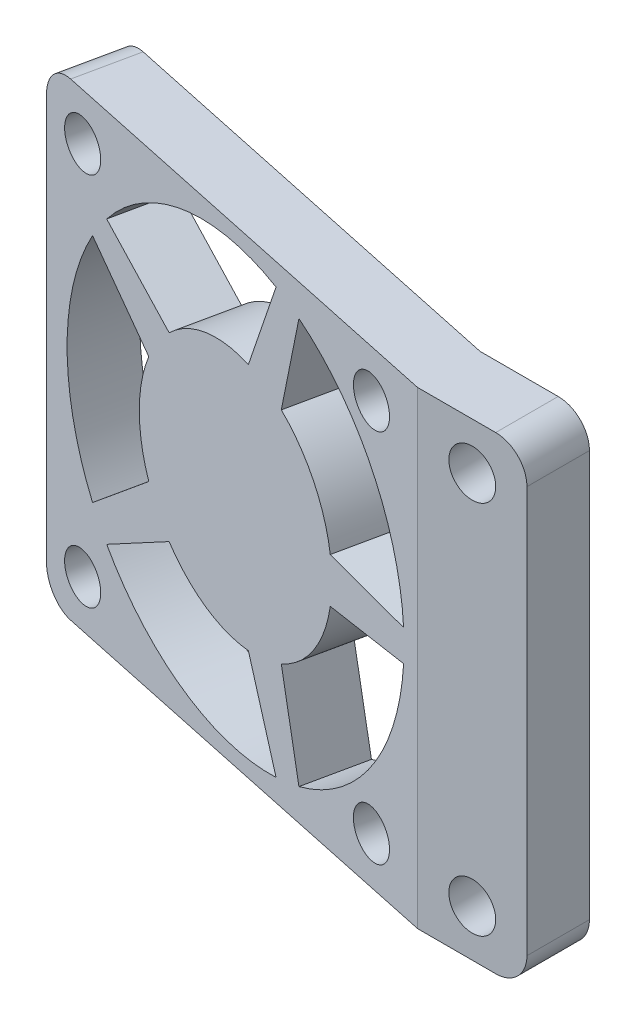
SolidWorks part; units mm, degrees
ref_plane "前基準面" through (0, 0, 0) normal (0, 0, 1) x (1, 0, 0)
ref_plane "上基準面" through (0, 0, 0) normal (0, 1, 0) x (1, 0, 0)
ref_plane "右基準面" through (0, 0, 0) normal (1, 0, 0) x (0, 0, -1)
sketch "草圖1" plane through (0, 0, 0) normal (0, 0, 1) x (1, 0, 0)
  line L1 (-3.5, 15) -> (3.5, 15)
  line L2 (-3.5, 15) -> (-3.5, -15)
  line L3 (-3.5, -15) -> (3.5, -15)
  line L4 (3.5, 15) -> (3.5, -15)
  point P4 (0, 15)
  point P6 (3.5, 0)
  dimension "D1" = 30
  dimension "D2" = 7
extrude "填料-伸長1" add sketch "草圖1" along normal blind 4
sketch "草圖2" plane through (0, -15, 0) normal (0, -1, 0) x (1, 0, 0)
  line L0 (-3.5, 4) -> (-33.6579, -2.4103)
  line L1 (-33.6579, -2.4103) -> (-32.8444, -6.2374)
  line L2 (-3.5, 4) -> (-3.5, 0)
  line L3 (-3.5, 4) -> (-3.5, 0)
  line L4 (-3.5, 0) -> (-32.8444, -6.2374)
  line L5 (-3.5, 0) -> (3.5, 0) construction
  line M8 (-3.5, 4) -> (-3.5, 0)
  dimension "D1" = 4
  dimension "D2" = 30
  dimension "D3" = 168
  dimension "D4" = 3.9126
extrude "填料-伸長2" add sketch "草圖2" against normal up to surface (30 mm away) contours L4 L0 L1 M8 up to face at (0, 15, 2)
sketch "草圖3" plane through (0, 0, 0) normal (0, 0, -1) x (-1, 0, 0)
  circle A0 centre (0, -12) radius 1.5
  circle A1 centre (0, 12) radius 1.5
  dimension "D1" = 3
  dimension "D2" = 3
  dimension "D3" = 12
  dimension "D4" = 12
extrude "除料-伸長2" cut sketch "草圖3" against normal through all
sketch "草圖4" plane through (-0.1513, 0, 0.7118) normal (0.2079, 0, -0.9781) x (-0.9781, 0, -0.2079)
  line L0 (33.4235, 0) -> (3.4235, 0) construction
  line L1 (33.4235, 15) -> (33.4235, -15) construction
  line L2 (3.4235, 15) -> (3.4235, -15) construction
  line L4 (3.4235, -15) -> (33.4235, -15) construction
  line L5 (18.4235, -15) -> (18.4235, 15) construction
  line L6 (33.4235, 15) -> (3.4235, 15) construction
  circle A0 centre (30.4235, -12) radius 1.5
  circle A1 centre (30.4235, 12) radius 1.5
  circle A2 centre (6.4235, 12) radius 1.5
  circle A3 centre (6.4235, -12) radius 1.5
  dimension "D3" = 3
  dimension "D1" = 3
  dimension "D2" = 3
extrude "除料-伸長3" cut sketch "草圖4" against normal through all
sketch "草圖5" plane through (-0.1513, 0, 0.7118) normal (0.2079, 0, -0.9781) x (-0.9781, 0, -0.2079)
  circle A0 centre (17.7171, 0) radius 14
  dimension "D1" = 28
extrude "除料-伸長4" cut sketch "草圖5" against normal through all
fillet "圓角1" radius 2 2 edges at (-33.2512, 15, -4.3238) (-33.2512, -15, -4.3238)
fillet "圓角2" radius 2 2 edges at (3.5, 15, 2) (3.5, -15, 2)
sketch "草圖6" [suppressed] plane through (0, 0, 0) normal (0, 0, -1) x (-1, 0, 0)
  circle A0 centre (0, -12) radius 3
  dimension "D1" = 6
sketch "草圖7" plane through (-0.9648, 0, 4.5389) normal (-0.2079, 0, 0.9781) x (0.9781, 0, 0.2079)
  line L0 (-3.7171, 0) -> (-9.7171, 0) construction
  line L1 (-3.7529, 1) -> (-9.8473, 1.4375)
  line L2 (-3.7529, -1) -> (-9.8473, -1.4375)
  line L3 (-12.4508, -12.9718) -> (-13.918, -7.0404)
  line L4 (-14.353, -13.5898) -> (-16.6523, -7.9288)
  line L5 (-28.4266, -9.017) -> (-23.2389, -5.7887)
  line L6 (-29.6022, -7.399) -> (-24.9288, -3.4628)
  line L7 (-29.6022, 7.399) -> (-24.9288, 3.4628)
  line L8 (-28.4266, 9.017) -> (-23.2389, 5.7887)
  line L9 (-14.353, 13.5898) -> (-16.6523, 7.9288)
  line L10 (-12.4508, 12.9718) -> (-13.918, 7.0404)
  arc A0 (-16.6523, 7.9288) -> (-23.2389, 5.7887) centre (-17.7171, 0) ccw
  circle A1 centre (-17.7171, 0) radius 14 construction
  arc A2 (-29.6022, -7.399) -> (-28.4266, -9.017) centre (-17.7171, 0) ccw
  arc A3 (-9.8473, 1.4375) -> (-13.918, 7.0404) centre (-17.7171, 0) ccw
  arc A4 (-13.918, -7.0404) -> (-9.8473, -1.4375) centre (-17.7171, 0) ccw
  arc A5 (-23.2389, -5.7887) -> (-16.6523, -7.9288) centre (-17.7171, 0) ccw
  arc A6 (-24.9288, 3.4628) -> (-24.9288, -3.4628) centre (-17.7171, 0) ccw
  arc A7 (-14.353, -13.5898) -> (-12.4508, -12.9718) centre (-17.7171, 0) ccw
  arc A8 (-3.7529, -1) -> (-3.7529, 1) centre (-17.7171, 0) ccw
  arc A9 (-12.4508, 12.9718) -> (-14.353, 13.5898) centre (-17.7171, 0) ccw
  arc A10 (-28.4266, 9.017) -> (-29.6022, 7.399) centre (-17.7171, 0) ccw
  point P31 (-17.7171, 0)
  dimension "D1" = 16
  dimension "D2" = 1
  dimension "D3" = 5
extrude "填料-伸長4" add sketch "草圖7" against normal up to surface (3.9126 mm away) up to face at (-31.1753, 0, -5.8826)
